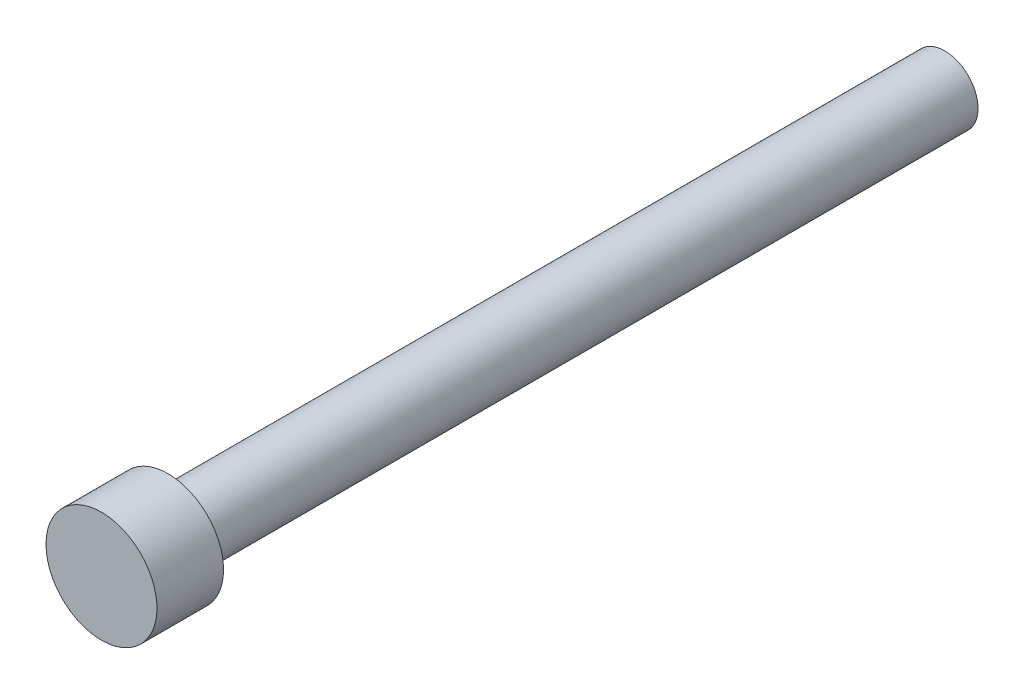
SolidWorks part; units mm, degrees
material "1.1191 (C45E)"
ref_plane "Front Plane" through (0, 0, 0) normal (0, 0, 1) x (1, 0, 0)
ref_plane "Top Plane" through (0, 0, 0) normal (0, 1, 0) x (1, 0, 0)
ref_plane "Right Plane" through (0, 0, 0) normal (1, 0, 0) x (0, 0, -1)
sketch "Sketch1" plane through (0, 0, 0) normal (0, 1, 0) x (1, 0, 0)
  line L0 (0, -6) -> (5, -6)
  line L1 (5, -6) -> (5, 0)
  line L2 (5, 0) -> (3, 0)
  line L3 (3, 0) -> (3, 70)
  line L4 (3, 70) -> (0, 70)
  line L5 (0, 70) -> (0, -6) construction
  line L6 (0, -6) -> (0, 70)
revolve "REV_ISO4762_M6x70_8.8" add sketch "Sketch1" angle 360 about L5
